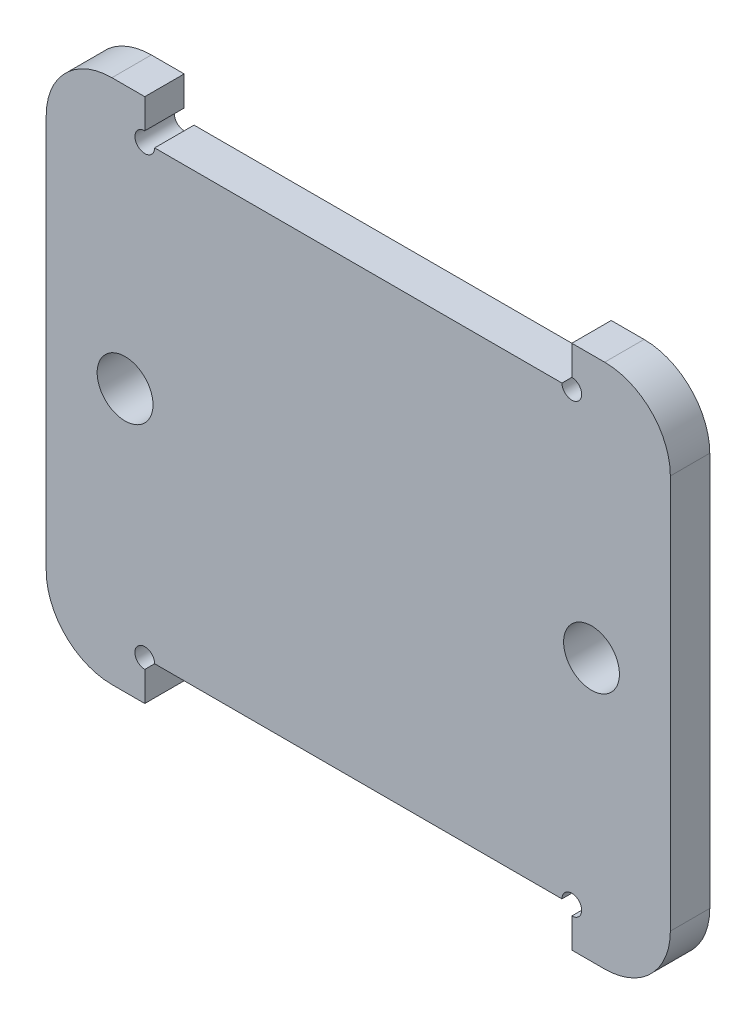
SolidWorks part; units mm, degrees
ref_plane "Front Plane" through (0, 0, 0) normal (0, 0, 1) x (1, 0, 0)
ref_plane "Top Plane" through (0, 0, 0) normal (0, 1, 0) x (1, 0, 0)
ref_plane "Right Plane" through (0, 0, 0) normal (1, 0, 0) x (0, 0, -1)
sketch "Sketch2" plane through (0, 0, 0) normal (0, 0, 1) x (1, 0, 0)
  line L0 (0, 40) -> (0, -40) construction
  line L1 (-47.5, -40) -> (-32.5, -40)
  line L2 (-47.5, -40) -> (-47.5, 40)
  line L3 (-47.5, 40) -> (-32.5, 40)
  line L4 (47.5, -40) -> (47.5, 40)
  line L5 (-47.5, -40) -> (47.5, 40) construction
  line L6 (-47.5, 40) -> (47.5, -40) construction
  line L7 (55, 0) -> (-55, 0) construction
  line L9 (-32.5, 40) -> (-32.5, 35.5)
  line L10 (-31, 34) -> (31, 34)
  line L11 (32.5, 40) -> (32.5, 35.5)
  line L12 (32.5, -40) -> (32.5, -35.5)
  line L13 (-31, -34) -> (31, -34)
  line L14 (-32.5, -40) -> (-32.5, -35.5)
  line L15 (32.5, 40) -> (47.5, 40)
  line L16 (32.5, -40) -> (47.5, -40)
  line L17 (0, -55) -> (0, 55) construction
  line L18 (-47.5, 0) -> (47.5, 0) construction
  arc A0 (-32.5, 35.5) -> (-31, 34) centre (-32.5, 34) ccw
  arc A1 (32.5, 35.5) -> (31, 34) centre (32.5, 34) cw
  arc A2 (32.5, -35.5) -> (31, -34) centre (32.5, -34) ccw
  arc A3 (-32.5, -35.5) -> (-31, -34) centre (-32.5, -34) cw
  circle A4 centre (-35.5, 0) radius 4.25
  circle A5 centre (35.5, 0) radius 4.25
  point P0 (0, 0)
  dimension "D5" = 1.5
  dimension "D6" = 8.5
  dimension "D1" = 95
  dimension "D2" = 80
  dimension "D3" = 6
  dimension "D4" = 65
  dimension "D7" = 71
extrude "Boss-Extrude1" add sketch "Sketch2" along normal blind 6
fillet "Fillet1" radius 10 4 edges at (-47.5, -40, 3) (47.5, -40, 3) (47.5, 40, 3) (-47.5, 40, 3)
